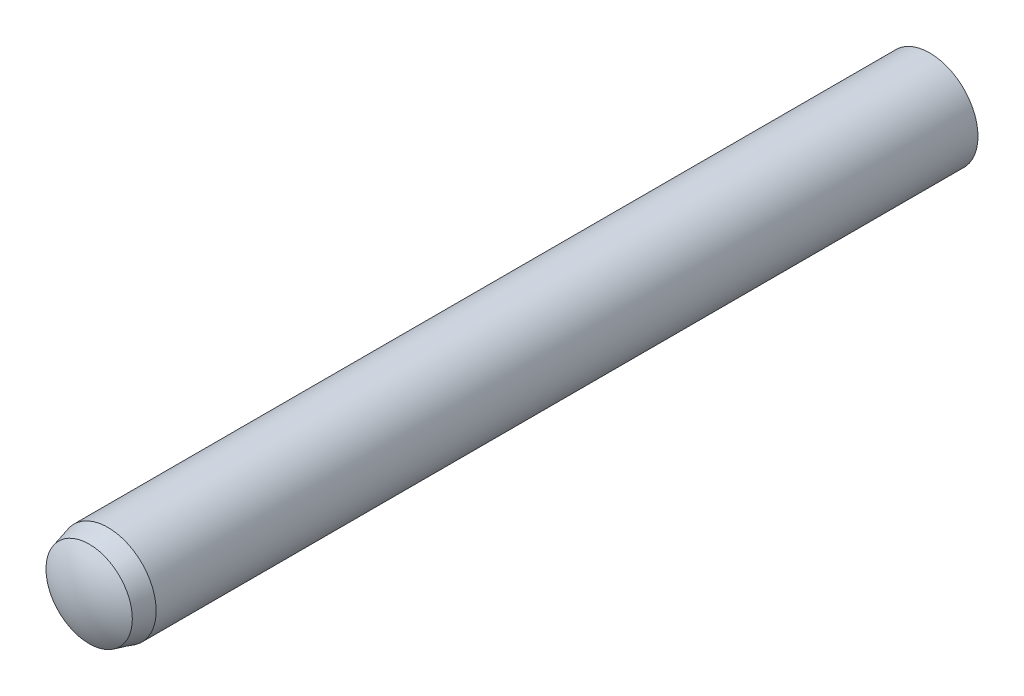
SolidWorks part; units mm, degrees
ref_plane "Front Plane" through (0, 0, 0) normal (0, 0, 1) x (1, 0, 0)
ref_plane "Top Plane" through (0, 0, 0) normal (0, 1, 0) x (1, 0, 0)
ref_plane "Right Plane" through (0, 0, 0) normal (1, 0, 0) x (0, 0, -1)
sketch "Sketch1" plane through (0, 0, 0) normal (0, 0, 1) x (1, 0, 0)
  circle A0 centre (0, 0) radius 5
  point P3 (0, 5)
  dimension "Diameter" = 10
sketch "Sketch2" plane through (0, 0, 0) normal (1, 0, 0) x (0, 0, -1)
  line L0 (-45, 0) -> (45, 0) construction
  line L1 (-45, 0) -> (-45, 5) construction
  line L2 (-45, 5) -> (45, 5)
  line L3 (45, 5) -> (45, 0) construction
  line L4 (-43.7, 4.4775) -> (-41.75, 5)
  arc A0 (-45, 0) -> (-43.7, 4.4775) centre (-36.6392, 0) cw
  arc A1 (45, 0) -> (43.5, 5) centre (35.9167, 0) ccw
  point P2 (0, 0)
  point P11 (-35, 0)
  point P13 (35, 0)
  dimension "Length" = 90
  dimension "D1" = 15
  dimension "D2" = 1.5
  dimension "D3" = 3.25
  dimension "D4" = 1.95
  dimension "D5" = 10
  dimension "D6" = 10
sketch "Sketch3" plane through (0, 0, 0) normal (1, 0, 0) x (0, 0, -1)
  line L0 (-45, 0) -> (45, 0) construction
  line L1 (-43.7, 4.4775) -> (-41.75, 5) construction
  line L2 (-45, 0) -> (45, 0)
  line L3 (-43.7, 4.4775) -> (-41.75, 5)
  line L4 (-41.75, 5) -> (43.5, 5)
  arc A0 (45, 0) -> (43.5, 5) centre (35.9167, 0) ccw construction
  arc A1 (-43.7, 4.4775) -> (-45, 0) centre (-36.6392, 0) ccw construction
  arc A2 (45, 0) -> (43.5, 5) centre (35.9167, 0) ccw
  arc A3 (-43.7, 4.4775) -> (-45, 0) centre (-36.6392, 0) ccw
revolve "Revolve1" add sketch "Sketch3" angle 360 about L2
equation "\"D2@Sketch2\" = \"Diameter@Sketch1\" * .15"
equation "\"D3@Sketch2\" = \"Diameter@Sketch1\" * .325"
equation "\"D4@Sketch2\" = \"D3@Sketch2\" * .6"
equation "\"D5@Sketch2\"=\"Diameter@Sketch1\""
equation "\"D6@Sketch2\"=\"D5@sketch2\""
